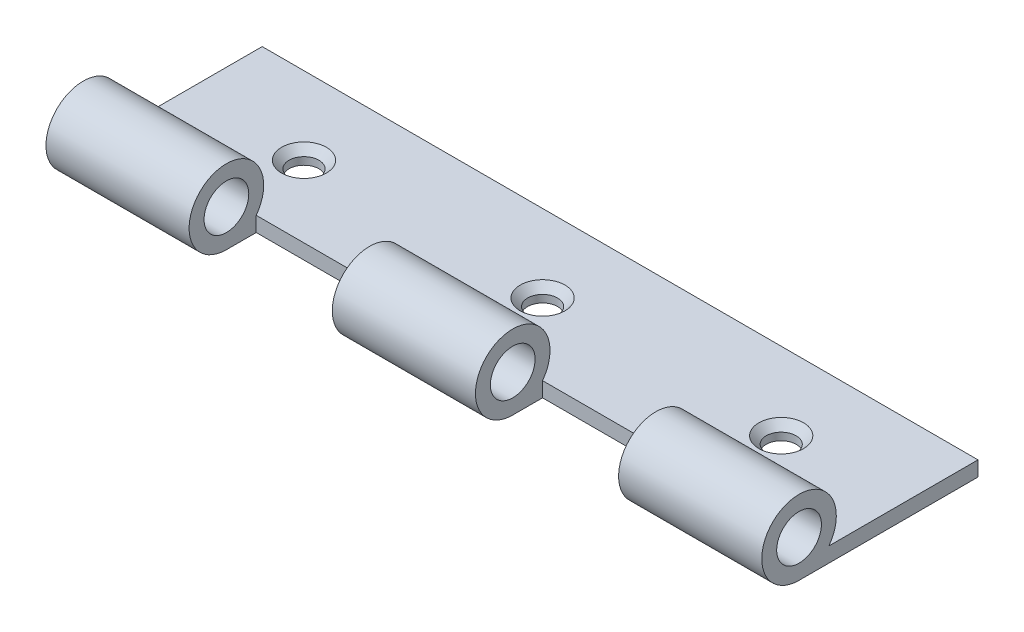
SolidWorks part; units mm, degrees
ref_plane "Front Plane" through (0, 0, 0) normal (0, 0, 1) x (1, 0, 0)
ref_plane "Top Plane" through (0, 0, 0) normal (0, 1, 0) x (1, 0, 0)
ref_plane "Right Plane" through (0, 0, 0) normal (1, 0, 0) x (0, 0, -1)
sketch "Sketch1" plane through (0, 0, 0) normal (0, 1, 0) x (1, 0, 0)
  line L1 (-38.1, -9.525) -> (38.1, -9.525)
  line L2 (-38.1, -9.525) -> (-38.1, 9.525)
  line L3 (-38.1, 9.525) -> (38.1, 9.525)
  line L4 (38.1, -9.525) -> (38.1, 9.525)
  line L5 (-38.1, -9.525) -> (38.1, 9.525) construction
  line L6 (-38.1, 9.525) -> (38.1, -9.525) construction
  point P0 (0, 0)
  dimension "D1" = 76.2
  dimension "D2" = 19.05
extrude "Boss-Extrude1" add sketch "Sketch1" along normal blind 1.5875
sketch "Sketch2" plane through (38.1, 0, 0) normal (1, 0, 0) x (0, 0, -1)
  circle A0 centre (-9.525, 3.9688) radius 3.9688
  circle A1 centre (-9.525, 3.9688) radius 2.3813
  dimension "D1" = 7.9375
  dimension "D2" = 4.7625
extrude "Boss-Extrude2" add sketch "Sketch2" against normal up to surface (76.2 mm away) up to face at (-38.1, 0.7937, 0)
ref_plane "Tangent Plane" through (0, 0, 5.5562) normal (0, 0, -1) x (-1, 0, 0)
sketch "Sketch4" plane through (0, 1.5875, 0) normal (0, 1, 0) x (1, 0, 0)
  line L0 (38.1, 1.275) -> (-49961.9, 1.275) construction
  line L2 (38.1, -6.35) -> (38.1, 9.525) construction
  line L3 (-38.1, 9.525) -> (-38.1, -6.35) construction
  line L5 (38.1, 9.525) -> (-38.1, 9.525) construction
  circle A0 centre (-25.4, 1.275) radius 1.5875
  point P4 (38.1, 1.5875)
  dimension "D1" = 12.7
  dimension "D2" = 8.25
extrude "Cut-Extrude1" cut sketch "Sketch4" against normal through all
chamfer "Chamfer1" distance 0.7937 1 edges at (-25.4, 1.5875, 0.3125)
pattern_linear "LPattern1" count 3 spacing 25.4 along (1, 0, 0) of "Chamfer1", "Cut-Extrude1"
sketch "Sketch5" plane through (38.1, 0, 0) normal (1, 0, 0) x (0, 0, -1)
  line L0 (-6.35, 1.5875) -> (-6.35, 0)
  line L3 (9.525, 1.5875) -> (-6.35, 1.5875)
  line L4 (-9.525, 0) -> (9.525, 0)
  line L5 (9.525, 0) -> (9.525, 1.5875)
  line L7 (-9.525, 0) -> (-6.35, 0)
  arc A1 (-6.35, 1.5875) -> (-9.525, 0) centre (-9.525, 3.9688) ccw
  arc A2 (-6.35, 1.5875) -> (-9.525, 0) centre (-9.525, 3.9688) ccw
  dimension "D1" = 0
extrude "Cut-Extrude2" cut sketch "Sketch5" against normal blind 15.24 from offset 15.24 offset against normal yes
pattern_linear "LPattern2" count 5 spacing 15.24 along (-1, 0, 0) skipping (1, 0), (3, 0) of "Cut-Extrude2"
